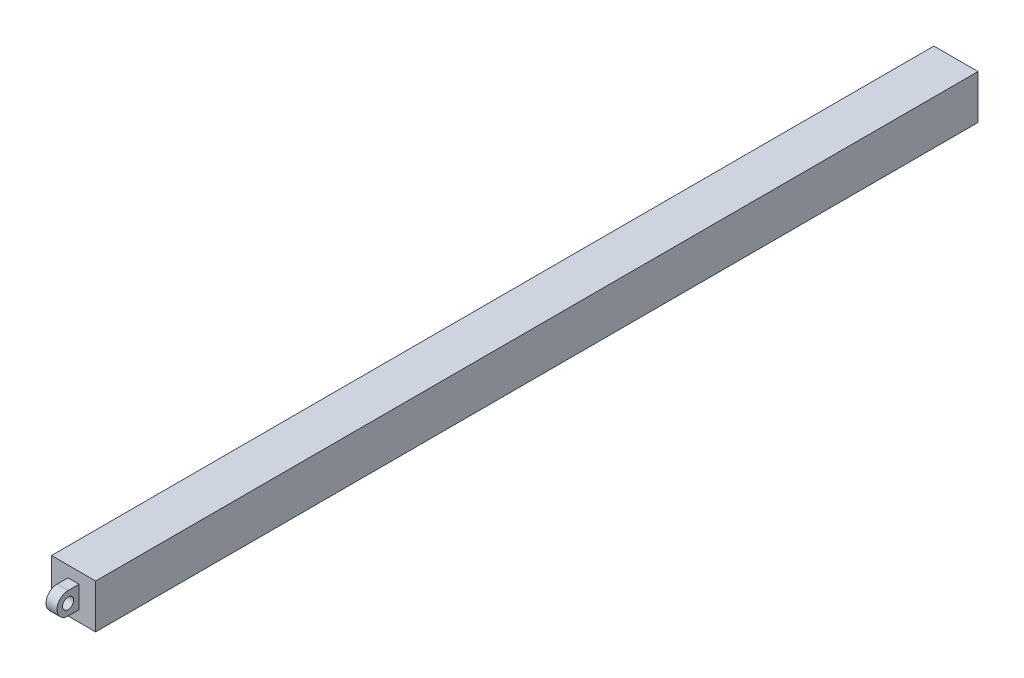
SolidWorks part; units mm, degrees
ref_plane "정면" through (0, 0, 0) normal (0, 0, 1) x (1, 0, 0)
ref_plane "윗면" through (0, 0, 0) normal (0, 1, 0) x (1, 0, 0)
ref_plane "우측면" through (0, 0, 0) normal (1, 0, 0) x (0, 0, -1)
sketch "스케치2" plane through (0, 0, 0) normal (1, 0, 0) x (0, 0, -1)
  line L0 (0, 5) -> (0, -5) construction
  line L1 (-100, 5) -> (100, 5)
  line L2 (-100, 5) -> (-100, -5)
  line L3 (-100, -5) -> (100, -5)
  line L4 (100, 5) -> (100, -5)
  line L5 (-100, 0) -> (100, 0) construction
  dimension "D1" = 10
  dimension "D2" = 200
extrude "보스-돌출1" add sketch "스케치2" along normal mid plane 10
sketch "스케치3" plane through (0, 0, 0) normal (1, 0, 0) x (0, 0, -1)
  line L0 (-100, 5) -> (-100, -5) construction
  line L1 (-102.5, 2.5) -> (-100, 2.5)
  line L2 (0, 0) -> (-168.2672, 0) construction
  line L3 (-102.5, -2.5) -> (-100, -2.5)
  line L4 (-100, 2.5) -> (-100, -2.5)
  arc A0 (-102.5, 2.5) -> (-102.5, -2.5) centre (-102.5, 0) ccw
  circle A1 centre (-102.5, 0) radius 1.25
  dimension "D3" = 2.5
  dimension "D1" = 5
  dimension "D2" = 2.5
extrude "보스-돌출2" add sketch "스케치3" along normal mid plane 2.5
